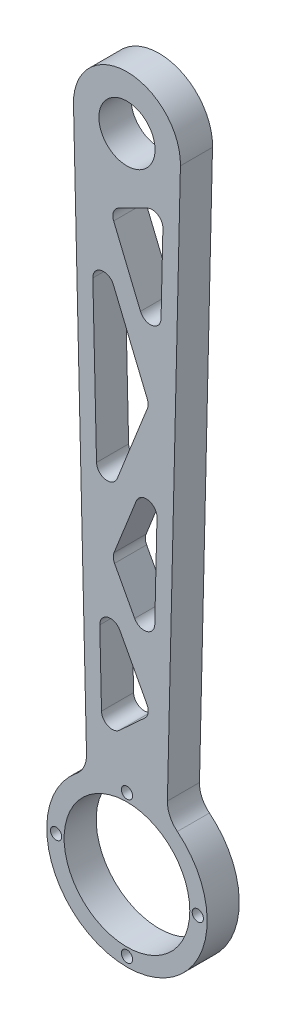
SolidWorks part; units mm, degrees
material "Thornel Mat VMA"
ref_plane "前视基准面" through (0, 0, 0) normal (0, 0, 1) x (1, 0, 0)
ref_plane "上视基准面" through (0, 0, 0) normal (0, 1, 0) x (1, 0, 0)
ref_plane "右视基准面" through (0, 0, 0) normal (1, 0, 0) x (0, 0, -1)
other "Configuration Table"
sketch "草图1" plane through (0, 0, 0) normal (0, 0, 1) x (1, 0, 0)
  line L1 (0, 0) -> (0, 240) construction
  line L2 (-15, 25.9808) -> (-19.9945, 239.5324)
  line L3 (15, 25.9808) -> (19.9945, 239.5324)
  line L4 (-13.5029, 240) -> (13.5029, 240) construction
  arc A1 (-15, 25.9808) -> (15, 25.9808) centre (0, 0) ccw
  arc A2 (19.9945, 239.5324) -> (-19.9945, 239.5324) centre (0, 240) ccw
  dimension "D1" = 15
  dimension "D2" = 60
  dimension "D3" = 40
  dimension "D4" = 240
  dimension "D5" = 15
extrude "凸台-拉伸1" add sketch "草图1" along normal blind 12
sketch "草图2" plane through (0, 0, 12) normal (0, 0, 1) x (1, 0, 0)
  circle A0 centre (0, 240) radius 10.5
  circle A1 centre (0, 0) radius 23.5
  dimension "D1" = 47
  dimension "D2" = 21
extrude "切除-拉伸1" cut sketch "草图2" against normal blind 39
fillet "圆角1" radius 10 2 edges at (15, 25.9808, 6) (-15, 25.9808, 6)
sketch "草图3" plane through (0, 0, 12) normal (0, 0, 1) x (1, 0, 0)
  circle A0 centre (0, 0) radius 26.5 construction
  circle A1 centre (0, 26.5) radius 2.1
  circle A2 centre (26.5, 0) radius 2.1
  circle A3 centre (0, -26.5) radius 2.1
  circle A4 centre (-26.5, 0) radius 2.1
  point P14 (0, 0)
  dimension "D1" = 53
  dimension "D2" = 4.2
  dimension "D3" = 4
extrude "切除-拉伸2" cut sketch "草图3" against normal blind 68
sketch "草图6" plane through (0, 0, 0) normal (0, 0, -1) x (-1, 0, 0)
  line L0 (-13.5974, 222.6244) -> (6.3961, 212.6438)
  line L1 (6.3961, 212.6438) -> (-12.3053, 167.3763)
  line L2 (-12.3053, 167.3763) -> (-13.5974, 222.6244)
  line L3 (-15.1258, 31.3599) -> (-19.9945, 239.5324) construction
  line L4 (13.2627, 208.313) -> (-8.2377, 156.2703)
  line L5 (-8.2377, 156.2703) -> (10.9206, 108.1714)
  line L6 (10.9206, 108.1714) -> (13.2627, 208.313)
  line L7 (-11.7459, 143.4586) -> (5.5253, 100.0975)
  line L8 (5.5253, 100.0975) -> (-10.0512, 70.9972)
  line L9 (-10.0512, 70.9972) -> (-11.7459, 143.4586)
  line L10 (-8.9482, 56.1057) -> (10.5551, 92.5422)
  line L11 (10.5551, 92.5422) -> (9.3106, 39.3326)
  line L12 (9.3106, 39.3326) -> (-8.9482, 56.1057)
  line L13 (19.9945, 239.5324) -> (15.1258, 31.3599) construction
  dimension "D1" = 6
  dimension "D2" = 8
  dimension "D3" = 6
  dimension "D4" = 8
  dimension "D5" = 6
  dimension "D6" = 8
  dimension "D7" = 6
extrude "切除-拉伸3" cut sketch "草图6" against normal through all
fillet "圆角3" radius 4 12 edges at (-6.3961, 212.6438, 6) (12.3053, 167.3763, 6) (8.9482, 56.1057, 6) (-10.5551, 92.5422, 6) (-9.3106, 39.3326, 6) (-10.9206, 108.1714, 6) (8.2377, 156.2703, 6) (-13.2627, 208.313, 6) (11.7459, 143.4586, 6) (-5.5253, 100.0975, 6) (10.0512, 70.9972, 6) (13.5974, 222.6244, 6)
